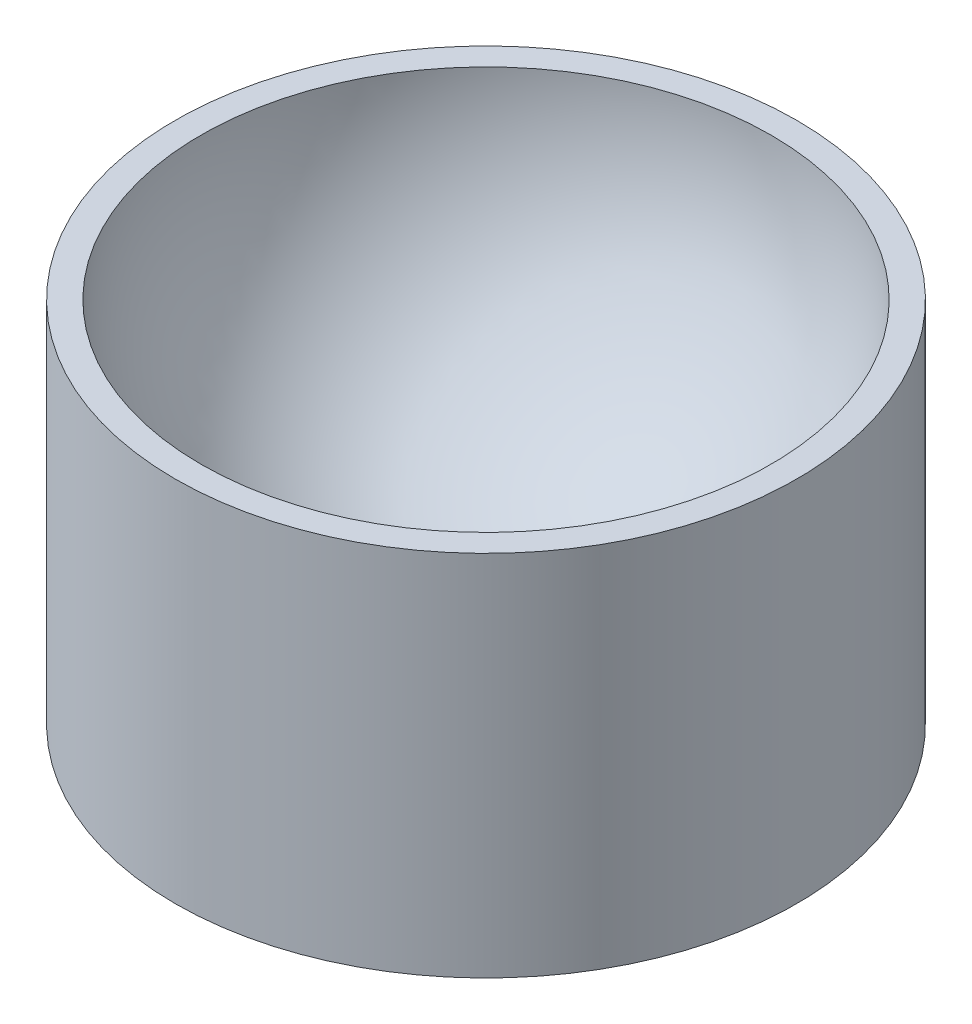
SolidWorks part; units mm, degrees
ref_plane "Front Plane" through (0, 0, 0) normal (0, 0, 1) x (1, 0, 0)
ref_plane "Top Plane" through (0, 0, 0) normal (0, 1, 0) x (1, 0, 0)
ref_plane "Right Plane" through (0, 0, 0) normal (1, 0, 0) x (0, 0, -1)
sketch "Sketch2" plane through (0, 0, 0) normal (0, 1, 0) x (1, 0, 0)
  line L1 (0, 7.5056) -> (-6.5, 3.7528)
  line L2 (-6.5, 3.7528) -> (-6.5, -3.7528)
  line L3 (-6.5, -3.7528) -> (0, -7.5056)
  line L4 (0, -7.5056) -> (6.5, -3.7528)
  line L5 (6.5, -3.7528) -> (6.5, 3.7528)
  line L6 (6.5, 3.7528) -> (0, 7.5056)
  circle A0 centre (0, 0) radius 54.5
  circle A1 centre (0, 0) radius 6.5 construction
  dimension "D1" = 109
  dimension "D2" = 13
extrude "Boss-Extrude1" add sketch "Sketch2" along normal blind 11.5
sketch "Sketch3" plane through (0, 0, 0) normal (0, -1, 0) x (1, 0, 0)
  circle A0 centre (0, 0) radius 8
  dimension "D1" = 16
extrude "Cut-Extrude1" cut sketch "Sketch3" against normal blind 7
sketch "Sketch4" plane through (0, 0, 0) normal (0, 0, 1) x (1, 0, 0)
  line L0 (0, 0) -> (0, 64.5) construction
  line L1 (4.05, 14.6643) -> (4.05, 11.5)
  line L2 (4.05, 11.5) -> (54.5, 11.5)
  line L4 (54.5, 11.5) -> (-54.5, 11.5) construction
  line L5 (54.5, 11.5) -> (54.5, 64.5)
  line L6 (54.5, 64.5) -> (50, 64.5)
  arc A0 (4.05, 14.6643) -> (50, 64.5) centre (0, 64.5) ccw
  dimension "D1" = 100
  dimension "D2" = 3
  dimension "D3" = 4.05
revolve "Revolve1" add sketch "Sketch4" angle 360 about L0
